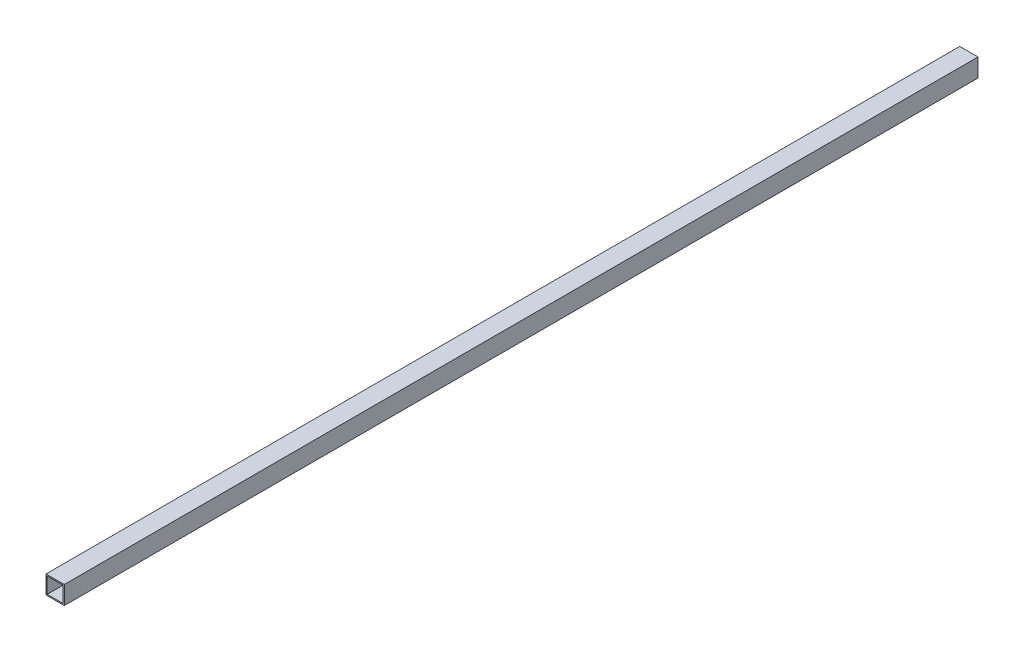
SolidWorks part; units mm, degrees
ref_plane "Спереди" through (0, 0, 0) normal (0, 0, 1) x (1, 0, 0)
ref_plane "Сверху" through (0, 0, 0) normal (0, 1, 0) x (1, 0, 0)
ref_plane "Справа" through (0, 0, 0) normal (1, 0, 0) x (0, 0, -1)
sketch "Эскиз1" plane through (0, 0, 0) normal (0, 0, 1) x (1, 0, 0)
  line L0 (0, 30) -> (2, 28)
  line L1 (0, 0) -> (30, 0)
  line L2 (0, 0) -> (0, 30)
  line L3 (0, 30) -> (30, 30)
  line L4 (30, 0) -> (30, 30)
  line L5 (30, 0) -> (28, 2)
  line L7 (2, 28) -> (28, 28)
  line L8 (2, 28) -> (2, 2)
  line L9 (2, 2) -> (28, 2)
  line L10 (28, 28) -> (28, 2)
  dimension "D1" = 2
  dimension "D2" = 2
  dimension "D3" = 2
  dimension "D4" = 2
  dimension "D5" = 30
extrude "Бобышка-Вытянуть1" add sketch "Эскиз1" along normal blind 1500 contours L9 L8 L0 L2 L1 L5 | L7 L10 L5 L4 L3 L0
